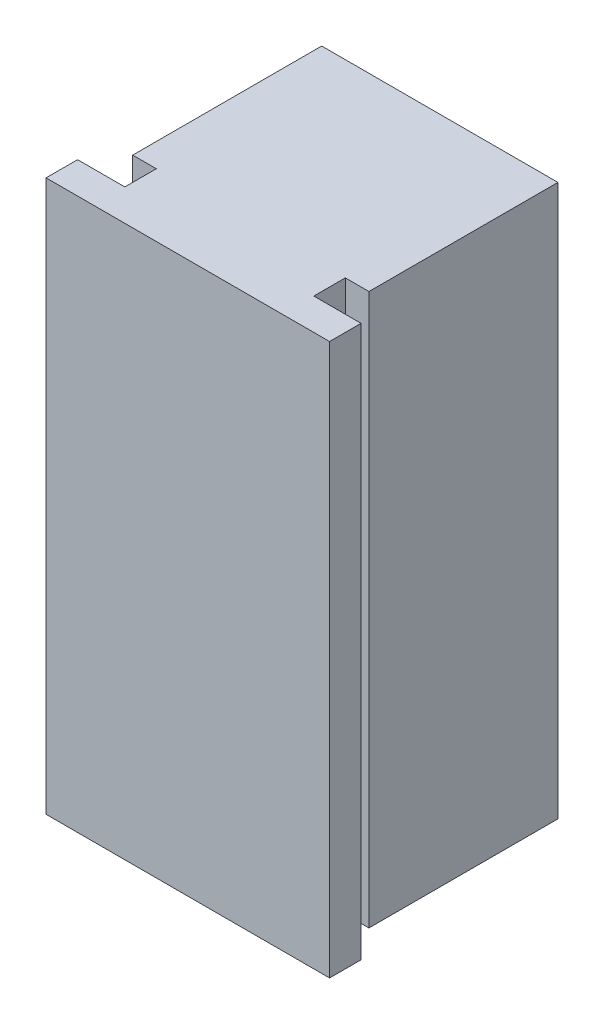
SolidWorks part; units mm, degrees
ref_plane "Front Plane" through (0, 0, 0) normal (0, 0, 1) x (1, 0, 0)
ref_plane "Top Plane" through (0, 0, 0) normal (0, 1, 0) x (1, 0, 0)
ref_plane "Right Plane" through (0, 0, 0) normal (1, 0, 0) x (0, 0, -1)
sketch "Sketch1" plane through (0, 0, 0) normal (0, 1, 0) x (1, 0, 0)
  line L0 (8.9355, 6.1935) -> (8.9355, -22) construction
  line L1 (1.4355, -15.1613) -> (1.4355, -3.1613)
  line L2 (-0.0645, -19.1613) -> (17.9355, -19.1613)
  line L3 (8.9355, -19.1613) -> (8.9355, -17.1613)
  line L4 (-0.0645, -17.1613) -> (17.9355, -17.1613)
  line L5 (17.9355, -19.1613) -> (17.9355, -17.1613)
  line L6 (2.9355, -17.1613) -> (14.9355, -17.1613)
  line L7 (8.9355, -17.1613) -> (8.9355, -15.1613)
  line L8 (2.9355, -15.1613) -> (14.9355, -15.1613)
  line L9 (14.9355, -17.1613) -> (14.9355, -15.1613)
  line L10 (1.4355, -15.1613) -> (16.4355, -15.1613)
  line L11 (8.9355, -15.1613) -> (8.9355, -3.1613)
  line L12 (1.4355, -3.1613) -> (16.4355, -3.1613)
  line L13 (16.4355, -15.1613) -> (16.4355, -3.1613)
  line L14 (2.9355, -17.1613) -> (2.9355, -15.1613)
  line L15 (-0.0645, -19.1613) -> (-0.0645, -17.1613)
  dimension "D1" = 2
  dimension "D2" = 2
  dimension "D3" = 16
  dimension "D4" = 9
  dimension "D5" = 6
  dimension "D6" = 7.5
extrude "Boss-Extrude1" add sketch "Sketch1" along normal blind 35 contours L12 L1 L10 L8 L11 | L10 L13 L12 L11 L8 | L4 L9 L8 L7 | L14 L4 L7 L8 | L15 L2 L3 L4 | L2 L5 L4 L3
sketch "Sketch2" plane through (0, 0, 3.1613) normal (0, 0, -1) x (-1, 0, 0)
  line L0 (-8.9355, 35) -> (-8.9355, 0) construction
  line L1 (-1.4355, 35) -> (-16.4355, 35) construction
  line L2 (-1.4355, 0) -> (-16.4355, 0) construction
  circle A0 centre (-8.9355, 17.5) radius 4.5
extrude "Cut-Extrude1" cut sketch "Sketch2" against normal blind 12
